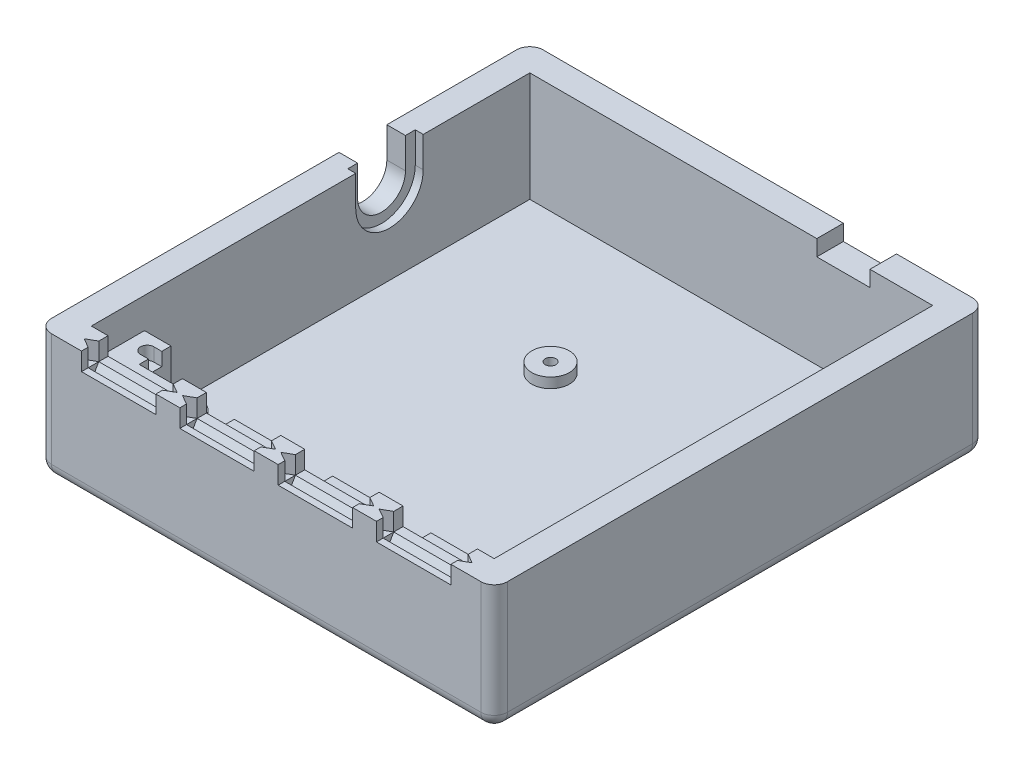
SolidWorks part; units mm, degrees
ref_plane "Front Plane" through (0, 0, 0) normal (0, 0, 1) x (1, 0, 0)
ref_plane "Top Plane" through (0, 0, 0) normal (0, 1, 0) x (1, 0, 0)
ref_plane "Right Plane" through (0, 0, 0) normal (1, 0, 0) x (0, 0, -1)
sketch "Sketch1" plane through (0, 0, 0) normal (0, 1, 0) x (1, 0, 0)
  line L0 (5, 4) -> (5, 10)
  line L1 (5, 10) -> (0, 10)
  line L2 (0, 10) -> (0, 82.5)
  line L3 (0, 82.5) -> (70.8, 82.5)
  line L4 (70.8, 82.5) -> (70.8, 79)
  line L5 (70.8, 79) -> (75.8, 79)
  line L6 (75.8, 79) -> (75.8, 4)
  line L7 (5, 4) -> (15.9, 4)
  line L8 (15.9, 4) -> (15.9, 0)
  line L9 (15.9, 0) -> (22.9, 0)
  line L10 (22.9, 0) -> (22.9, 4)
  line L11 (22.9, 4) -> (34.4, 4)
  line L12 (34.4, 4) -> (34.4, 0)
  line L13 (34.4, 0) -> (41.4, 0)
  line L14 (41.4, 0) -> (41.4, 4)
  line L15 (41.4, 4) -> (52.9, 4)
  line L16 (52.9, 4) -> (52.9, 0)
  line L17 (52.9, 0) -> (59.9, 0)
  line L18 (59.9, 0) -> (59.9, 4)
  line L19 (59.9, 4) -> (75.8, 4)
  line L20 (19.4, 27.0002) -> (19.4, -18.5168) construction
  line L21 (37.9, 24.8892) -> (37.9, -19.4403) construction
  line L22 (56.4, 24.8892) -> (56.4, -19.4529) construction
  line L23 (-5, 87.5) -> (-5, -5)
  line L24 (-5, -5) -> (80.8, -5)
  line L25 (80.8, -5) -> (80.8, 87.5)
  line L26 (80.8, 87.5) -> (-5, 87.5)
  dimension "D1" = 82.5
  dimension "D2" = 75.8
  dimension "D3" = 3.5
  dimension "D4" = 5
  dimension "D5" = 7
  dimension "D6" = 7
  dimension "D7" = 7
  dimension "D8" = 19.4
  dimension "D9" = 18.5
  dimension "D10" = 18.5
  dimension "D11" = 5
  dimension "D12" = 4
  dimension "D13" = 6
  dimension "D14" = 5
  dimension "D15" = 5
  dimension "D16" = 5
  dimension "D17" = 5
extrude "Boss-Extrude1" add sketch "Sketch1" along normal blind 14.859
sketch "Sketch2" plane through (0, 0, 0) normal (0, 1, 0) x (1, 0, 0)
  line L0 (-5, 87.5) -> (-5, -5) construction
  line L1 (-5, 87.5) -> (80.8, 87.5)
  line L2 (-5, 87.5) -> (-5, -5)
  line L3 (-5, -5) -> (80.8, -5)
  line L4 (80.8, 87.5) -> (80.8, -5)
  line L5 (80.8, 87.5) -> (-5, 87.5) construction
  line L6 (80.8, -5) -> (80.8, 87.5) construction
  line L7 (-5, -5) -> (80.8, -5) construction
  circle A0 centre (3.5, 13.5) radius 1
  circle A1 centre (19.4, 3.5) radius 1
  circle A2 centre (37.9, 3.5) radius 1
  circle A3 centre (56.4, 3.5) radius 1
  circle A4 centre (30.3, 56.1) radius 1
  circle A5 centre (71.8, 75.5) radius 1
  dimension "D3" = 2
  dimension "D1" = 3.5
  dimension "D2" = 13.5
  dimension "D4" = 19.4
  dimension "D5" = 18.5
  dimension "D6" = 18.5
  dimension "D7" = 3.5
  dimension "D8" = 56.1
  dimension "D9" = 30.3
  dimension "D10" = 71.8
  dimension "D11" = 75.5
extrude "Boss-Extrude2" add sketch "Sketch2" against normal blind 3.175
ref_plane "Plane1" through (0, 14.859, 0) normal (0, 1, 0) x (1, 0, 0)
sketch "Sketch4" plane through (0, 14.859, 0) normal (0, 1, 0) x (1, 0, 0)
  line L1 (0, 0) -> (75.8, 0)
  line L2 (0, 0) -> (0, 82.5)
  line L3 (0, 82.5) -> (75.8, 82.5)
  line L4 (75.8, 0) -> (75.8, 82.5)
  line L5 (-5, -5) -> (80.8, -5)
  line L6 (-5, -5) -> (-5, 87.5)
  line L7 (-5, 87.5) -> (80.8, 87.5)
  line L8 (80.8, -5) -> (80.8, 87.5)
  dimension "D1" = 82.5
  dimension "D2" = 75.8
  dimension "D3" = 5
  dimension "D4" = 5
  dimension "D5" = 5
  dimension "D6" = 5
extrude "Boss-Extrude3" add sketch "Sketch4" along normal blind 5.75
sketch "Sketch3" plane through (0, 0, 0) normal (1, 0, 0) x (0, 0, -1)
  line L0 (60.6, 14.859) -> (60.6, 20.609)
  line L1 (87.5, 20.609) -> (-5, 20.609) construction
  line L2 (51.6, 14.859) -> (51.6, 20.609)
  line L3 (60.6, 20.609) -> (51.6, 20.609)
  circle A0 centre (56.1, 14.859) radius 4.5 construction
  arc A1 (60.6, 14.859) -> (51.6, 14.859) centre (56.1, 14.859) cw
  dimension "D1" = 9
  dimension "D2" = 56.1
  dimension "D3" = 14.859
extrude "Cut-Extrude1" cut sketch "Sketch3" against normal through all
sketch "Sketch5" plane through (0, 0, 0) normal (0, 0, 1) x (1, 0, 0)
  line L1 (3.15, 25.25) -> (17.15, 25.25)
  line L2 (3.15, 25.25) -> (3.15, 17.25)
  line L3 (3.15, 17.25) -> (17.15, 17.25)
  line L4 (17.15, 25.25) -> (17.15, 17.25)
  line L5 (21.65, 25.25) -> (35.65, 25.25)
  line L6 (21.65, 25.25) -> (21.65, 17.25)
  line L7 (21.65, 17.25) -> (35.65, 17.25)
  line L8 (35.65, 25.25) -> (35.65, 17.25)
  line L9 (40.15, 25.25) -> (54.15, 25.25)
  line L10 (40.15, 25.25) -> (40.15, 17.25)
  line L11 (40.15, 17.25) -> (54.15, 17.25)
  line L12 (54.15, 25.25) -> (54.15, 17.25)
  line L13 (72.65, 25.25) -> (58.65, 25.25)
  line L14 (72.65, 25.25) -> (72.65, 17.25)
  line L15 (72.65, 17.25) -> (58.65, 17.25)
  line L16 (58.65, 25.25) -> (58.65, 17.25)
  point P16 (10.15, 17.25)
  point P17 (28.65, 17.25)
  point P18 (47.15, 17.25)
  point P19 (65.65, 17.25)
  dimension "D1" = 10.15
  dimension "D2" = 18.5
  dimension "D3" = 18.5
  dimension "D4" = 18.5
  dimension "D5" = 14
  dimension "D6" = 14
  dimension "D7" = 14
  dimension "D8" = 14
  dimension "D9" = 17.25
  dimension "D10" = 8
extrude "Cut-Extrude2" cut sketch "Sketch5" along normal through all
sketch "Sketch6" plane through (0, 0, 0) normal (0, 0, 1) x (1, 0, 0)
  line L1 (54, 17.63) -> (64, 17.63)
  line L4 (64, 17.63) -> (64, 23.63)
  line L5 (64, 23.63) -> (54, 23.63)
  line L6 (54, 23.63) -> (54, 17.63)
  point P0 (59, 17.63)
  dimension "D1" = 59
  dimension "D2" = 10
  dimension "D3" = 6
  dimension "D4" = 17.63
extrude "Cut-Extrude3" cut sketch "Sketch6" against normal through all
sketch "Sketch7" plane through (0, 0, 0) normal (0, 1, 0) x (1, 0, 0)
  line L0 (0, 13.5) -> (0, 10)
  line L1 (0, 51.6) -> (0, 0) construction
  line L2 (0, 10) -> (3.5, 10)
  line L3 (0, 10) -> (5, 10) construction
  line L4 (15.9, 3.5) -> (15.9, 0)
  line L5 (15.9, 4) -> (15.9, 0) construction
  line L6 (15.9, 0) -> (22.9, 0)
  line L7 (22.9, 0) -> (22.9, 3.5)
  line L8 (22.9, 0) -> (22.9, 4) construction
  line L9 (34.4, 3.5) -> (34.4, 0)
  line L10 (34.4, 4) -> (34.4, 0) construction
  line L11 (21.65, 0) -> (35.65, 0) construction
  line L12 (22.9, 0) -> (34.4, 0) construction
  line L13 (34.4, 0) -> (41.4, 0)
  line L14 (41.4, 0) -> (41.4, 3.5)
  line L15 (41.4, 0) -> (41.4, 4) construction
  line L16 (52.9, 3.5) -> (52.9, 0)
  line L17 (52.9, 4) -> (52.9, 0) construction
  line L18 (52.9, 0) -> (59.9, 0)
  line L19 (59.9, 0) -> (59.9, 3.5)
  line L20 (59.9, 0) -> (59.9, 4) construction
  line L21 (75.8, 79) -> (69.8635, 79)
  line L22 (75.8, 79) -> (70.8, 79) construction
  line L23 (75.8, 79) -> (75.8, 75.5)
  line L24 (75.8, 0) -> (75.8, 82.5) construction
  circle A0 centre (30.3, 56.1) radius 3.54
  circle A1 centre (30.3, 56.1) radius 1
  circle A2 centre (3.5, 13.5) radius 1
  arc A3 (0, 13.5) -> (3.5, 10) centre (3.5, 13.5) cw
  circle A4 centre (19.4, 3.5) radius 1
  arc A5 (15.9, 3.5) -> (22.9, 3.5) centre (19.4, 3.5) cw
  circle A6 centre (37.9, 3.5) radius 1
  arc A7 (34.4, 3.5) -> (41.4, 3.5) centre (37.9, 3.5) cw
  circle A8 centre (56.4, 3.5) radius 1
  arc A9 (52.9, 3.5) -> (59.9, 3.5) centre (56.4, 3.5) cw
  circle A10 centre (71.8, 75.5) radius 1
  arc A11 (75.8, 75.5) -> (69.8635, 79) centre (71.8, 75.5) cw
  dimension "D1" = 2.54
  dimension "D2" = 2
  dimension "D3" = 2
  dimension "D4" = 2
  dimension "D5" = 2
  dimension "D7" = 2
  dimension "D9" = 2
extrude "Boss-Extrude4" add sketch "Sketch7" along normal blind 1.9
fillet "Fillet1" radius 2.5 1 edges at (-5, 8.717, 5)
fillet "Fillet2" radius 2.5 1 edges at (80.8, 8.717, 5)
fillet "Fillet3" radius 2.5 1 edges at (80.8, 8.717, -87.5)
fillet "Fillet4" radius 2.5 1 edges at (-5, 8.717, -87.5)
fillet "Fillet5" radius 2.5 8 edges at (80.0678, -3.175, 4.2678) (37.9, -3.175, 5) (-4.2678, -3.175, 4.2678) (-5, -3.175, -41.25) (-4.2678, -3.175, -86.7678) (37.9, -3.175, -87.5) (80.0678, -3.175, -86.7678) (80.8, -3.175, -41.25)
sketch "Sketch8" plane through (0, 0, 0) normal (1, 0, 0) x (0, 0, -1)
  line L0 (62.45, 14.855) -> (62.45, 21.205)
  line L1 (49.75, 14.855) -> (49.75, 21.205)
  line L2 (49.75, 21.205) -> (62.45, 21.205)
  circle A0 centre (56.1, 14.855) radius 6.35 construction
  arc A1 (49.75, 14.855) -> (62.45, 14.855) centre (56.1, 14.855) ccw
  dimension "D3" = 12.7
  dimension "D1" = 56.1
  dimension "D2" = 14.855
extrude "Cut-Extrude4" cut sketch "Sketch8" against normal blind 1.5
ref_plane "Plane2" through (0, 20.609, 0) normal (0, 1, 0) x (1, 0, 0)
sketch "Sketch9" plane through (0, 20.609, 0) normal (0, 1, 0) x (1, 0, 0)
  line L0 (3.15, -5) -> (3.15, 0) construction
  line L1 (3.15, -1.75) -> (3.15, -3.75)
  line L2 (3.15, 0) -> (3.15, -5) construction
  line L3 (3.15, -3.75) -> (1.4, -2.75)
  line L4 (1.4, -2.75) -> (3.15, -1.75)
  line L5 (17.15, -1.75) -> (17.15, -3.75)
  line L6 (17.15, -5) -> (17.15, 0) construction
  line L7 (17.15, -3.75) -> (18.9, -2.75)
  line L8 (18.9, -2.75) -> (17.15, -1.75)
  line L9 (21.65, -1.75) -> (21.65, -3.75)
  line L10 (21.65, 0) -> (21.65, -5) construction
  line L11 (21.65, -3.75) -> (19.9, -2.75)
  line L12 (19.9, -2.75) -> (21.65, -1.75)
  line L13 (35.65, -1.75) -> (37.4, -2.75)
  line L14 (35.65, -5) -> (35.65, 0) construction
  line L15 (37.4, -2.75) -> (35.65, -3.75)
  line L16 (35.65, -5) -> (35.65, 0) construction
  line L17 (35.65, -3.75) -> (35.65, -1.75)
  line L18 (40.15, -1.75) -> (38.4, -2.75)
  line L19 (40.15, -5) -> (40.15, 0) construction
  line L20 (38.4, -2.75) -> (40.15, -3.75)
  line L21 (40.15, -3.75) -> (40.15, -1.75)
  line L22 (54.15, -1.75) -> (54.15, -3.75)
  line L23 (54.15, -5) -> (54.15, 0) construction
  line L24 (54.15, -3.75) -> (55.9, -2.75)
  line L25 (55.9, -2.75) -> (54.15, -1.75)
  line L26 (58.65, -1.75) -> (58.65, -3.75)
  line L27 (58.65, -5) -> (58.65, 0) construction
  line L28 (58.65, -3.75) -> (56.9, -2.75)
  line L29 (56.9, -2.75) -> (58.65, -1.75)
  line L30 (72.65, -1.75) -> (72.65, -3.75)
  line L31 (72.65, -5) -> (72.65, 0) construction
  line L32 (72.65, -5) -> (72.65, 0) construction
  line L33 (72.65, -3.75) -> (74.4, -2.75)
  line L34 (74.4, -2.75) -> (72.65, -1.75)
  point P0 (3.15, -2.75)
  dimension "D1" = 1.75
  dimension "D2" = 1
  dimension "D3" = 1
  dimension "D4" = 1.75
  dimension "D5" = 1.75
  dimension "D6" = 1.75
  dimension "D7" = 1.75
  dimension "D8" = 1.75
  dimension "D9" = 1.75
  dimension "D10" = 1.75
  dimension "D11" = 2.75
extrude "Cut-Extrude5" cut sketch "Sketch9" against normal blind 4
sketch "Sketch10" plane through (0, 0, 0) normal (1, 0, 0) x (0, 0, -1)
  line L4 (-3.75, 17.25) -> (-1.75, 17.25)
  line L5 (-1.75, 17.25) -> (-2.75, 15.5)
  line L6 (-2.75, 15.5) -> (-3.75, 17.25)
  point P7 (-2.75, 17.25)
  dimension "D1" = 2.75
  dimension "D2" = 17.25
  dimension "D5" = 1.75
  dimension "D6" = 2
extrude "Cut-Extrude7" cut sketch "Sketch10" along normal blind 73.9
sketch "Sketch12" plane through (0, 0, 0) normal (0, 0, 1) x (1, 0, 0)
  line L1 (3.15, 17.25) -> (-1.351, 17.25)
  line L2 (3.15, 17.25) -> (3.15, 13.25)
  line L3 (3.15, 13.25) -> (-1.351, 13.25)
  line L4 (-1.351, 17.25) -> (-1.351, 13.25)
  line L5 (21.65, 17.25) -> (17.149, 17.25)
  line L6 (21.65, 17.25) -> (21.65, 13.25)
  line L7 (21.65, 13.25) -> (17.149, 13.25)
  line L8 (17.149, 17.25) -> (17.149, 13.25)
  line L9 (40.15, 17.25) -> (35.649, 17.25)
  line L10 (40.15, 17.25) -> (40.15, 13.25)
  line L11 (40.15, 13.25) -> (35.649, 13.25)
  line L12 (35.649, 17.25) -> (35.649, 13.25)
  line L13 (58.65, 17.25) -> (54.149, 17.25)
  line L14 (58.65, 17.25) -> (58.65, 13.25)
  line L15 (58.65, 13.25) -> (54.149, 13.25)
  line L16 (54.149, 17.25) -> (54.149, 13.25)
  line L17 (72.65, 17.25) -> (77.151, 17.25)
  line L18 (72.65, 17.25) -> (72.65, 13.25)
  line L19 (72.65, 13.25) -> (77.151, 13.25)
  line L20 (77.151, 17.25) -> (77.151, 13.25)
  dimension "D1" = 4
  dimension "D2" = 4.501
extrude "Boss-Extrude8" add sketch "Sketch12" along normal blind 5
sketch "Sketch13" plane through (0, 14.859, 0) normal (0, 1, 0) x (1, 0, 0)
  line L0 (3.5, 8.25) -> (5, 8.25)
  line L1 (5, 10) -> (5, 4) construction
  line L2 (5, 8.25) -> (5, 5.75)
  line L3 (5, 10) -> (5, 4) construction
  line L4 (5, 5.75) -> (3.5, 5.75)
  arc A0 (3.5, 8.25) -> (3.5, 5.75) centre (3.5, 7) ccw
  point P0 (3.5, 7)
  dimension "D3" = 1.25
  dimension "D1" = 7
  dimension "D2" = 3.5
extrude "Cut-Extrude8" cut sketch "Sketch13" against normal blind 2.5
